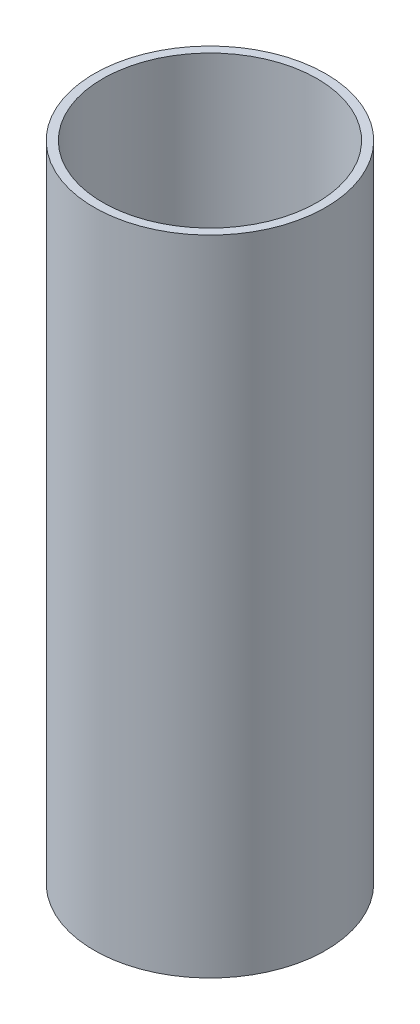
SolidWorks part; units mm, degrees
material "Thornel Mat VMA"
ref_plane "Front Plane" through (0, 0, 0) normal (0, 0, 1) x (1, 0, 0)
ref_plane "Top Plane" through (0, 0, 0) normal (0, 1, 0) x (1, 0, 0)
ref_plane "Right Plane" through (0, 0, 0) normal (1, 0, 0) x (0, 0, -1)
sketch "Sketch2" plane through (0, 0, 0) normal (0, 1, 0) x (1, 0, 0)
  circle A0 centre (0, 0) radius 13.716
  circle A1 centre (0, 0) radius 12.7
  dimension "D1" = 25.4
  dimension "D2" = 1.016
extrude "Boss-Extrude1" add sketch "Sketch2" along normal blind 76.2
